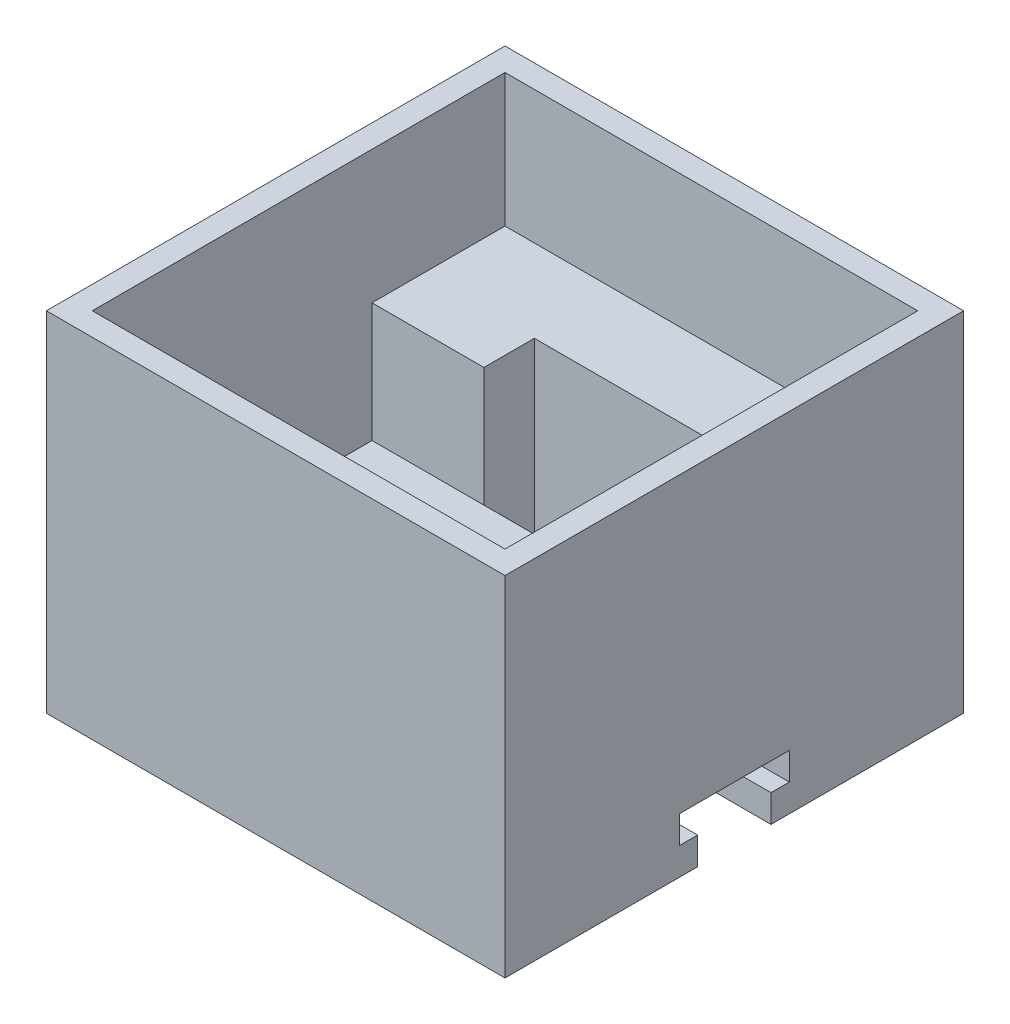
SolidWorks part; units mm, degrees
ref_plane "Front Plane" through (0, 0, 0) normal (0, 0, 1) x (1, 0, 0)
ref_plane "Top Plane" through (0, 0, 0) normal (0, 1, 0) x (1, 0, 0)
ref_plane "Right Plane" through (0, 0, 0) normal (1, 0, 0) x (0, 0, -1)
sketch "Sketch1" plane through (0, 0, 0) normal (0, 1, 0) x (1, 0, 0)
  line L1 (25, 25) -> (-25, 25)
  line L2 (25, 25) -> (25, -25)
  line L3 (25, -25) -> (-25, -25)
  line L4 (-25, 25) -> (-25, -25)
  line L5 (25, 25) -> (-25, -25) construction
  line L6 (25, -25) -> (-25, 25) construction
  point P0 (0, 0)
  dimension "D1" = 50
  dimension "D2" = 50
extrude "Boss-Extrude1" add sketch "Sketch1" along normal blind 38
shell "Shell1" thickness 2.5
sketch "Sketch2" plane through (0, 2.5, 0) normal (0, 1, 0) x (1, 0, 0)
  line L1 (9.676, 17.0496) -> (-10.324, 17.0496) construction
  line L2 (9.676, 17.0496) -> (9.676, -16.9504) construction
  line L3 (-10.3, -16.9504) -> (-10.324, -16.9504) construction
  line L4 (-10.324, 17.0496) -> (-10.324, -16.9504) construction
  line L5 (-10.3, 8) -> (-22.5, 8)
  line L6 (-22.5, 22.5) -> (-22.5, -22.5) construction
  line L7 (-22.5, 8) -> (-22.5, 22.5)
  line L8 (-22.5, 22.5) -> (0, 22.5)
  line L9 (22.5, 22.5) -> (-22.5, 22.5) construction
  line L11 (-10.3, 8) -> (-10.3, 13.5)
  line L12 (-10.3, 13.5) -> (0, 13.5)
  line L13 (22.5, -22.5) -> (22.5, 22.5) construction
  line L14 (22.5, 8) -> (22.5, 22.5)
  line L15 (10.3, 8) -> (22.5, 8)
  line L16 (10.3, 8) -> (10.3, 13.5)
  line L17 (10.3, 13.5) -> (0, 13.5)
  line L19 (22.5, 22.5) -> (0, 22.5)
  line L20 (10.3, -13.6) -> (22.5, -13.6)
  line L22 (10.0266, -9.8035) -> (10.0241, -17.0234) construction
  line L27 (-22.5, -13.6) -> (-22.5, -22.5)
  line L28 (-10.3, -13.6) -> (-22.5, -13.6)
  line L29 (-10.3, -13.6) -> (-10.3, -20.79)
  line L30 (-10.3, -20.79) -> (0.1901, -20.79)
  line L32 (-22.5, -22.5) -> (0.1901, -22.5)
  line L33 (-10.324, 17.0496) -> (-10.324, 9.8396) construction
  line L34 (10.3, -13.6) -> (10.3, -20.79)
  line L35 (9.676, -16.9504) -> (-10.3, -16.9504) construction
  line L36 (10.3, -20.79) -> (0.1901, -20.79)
  line L38 (22.5, -22.5) -> (0.1901, -22.5)
  line L39 (22.5, -13.6) -> (22.5, -22.5)
  line L40 (22.5, -22.5) -> (22.5, 22.5) construction
  point P0 (0, 0)
  line M19 (-22.5, 22.5) -> (-22.5, -22.5)
  line M20 (-22.5, -22.5) -> (22.5, -22.5)
  line M21 (22.5, -22.5) -> (22.5, 22.5)
  line M22 (22.5, 22.5) -> (-22.5, 22.5)
  dimension "D1" = 34
  dimension "D3" = 12.2
  dimension "D4" = 12.2
  dimension "D5" = 14.5
  dimension "D6" = 8.9
  dimension "D7" = 9
  dimension "D9" = 1.71
sketch "Sketch3" plane through (0, 2.5, 0) normal (0, 1, 0) x (1, 0, 0)
  line L0 (22.5, -8) -> (22.5, 8)
  line L1 (22.5, -22.5) -> (22.5, 22.5) construction
  line L2 (22.5, 8) -> (22.5, -8)
  line L3 (22.5, 8) -> (-22.5, 8)
  line L4 (22.5, -8) -> (-22.5, -8)
  line L5 (-22.5, 8) -> (-22.5, -8)
  line L6 (-22.5, 22.5) -> (-22.5, -22.5) construction
  point P4 (22.5, 0)
  point P6 (22.5, 0)
  line M6 (-22.5, 22.5) -> (-22.5, -22.5)
  line M8 (22.5, -22.5) -> (22.5, 22.5)
  dimension "D1" = 16
extrude "Boss-Extrude2" add sketch "Sketch2" along normal blind 21 contours L34 L36 L30 L29 L28 L20 M19 M20 M21 | L17 L16 L15 L5 L11 L12 M21 M22 M19
extrude "Boss-Extrude3" add sketch "Sketch3" along normal blind 8 contours L4 L3 M8 M6
sketch "Sketch4" plane through (0, 0, 0) normal (0, -1, 0) x (1, 0, 0)
  line L4 (25, -4) -> (-7.5, -4)
  line L5 (22.5, -8) -> (25, -8) construction
  line L6 (22.5, 8) -> (25, 8) construction
  line L7 (22.5, 0) -> (25, 0)
  line L8 (25, 25) -> (25, -25) construction
  line L9 (-7.5, -4) -> (-7.5, 4)
  line L10 (-7.5, 4) -> (25, 4)
  line L11 (25, 4) -> (25, -4)
  point P10 (25, 0)
  dimension "D1" = 8
  dimension "D2" = 32.5
extrude "Cut-Extrude1" cut sketch "Sketch4" against normal blind 3
ref_plane "Plane1" through (0, 3, 0) normal (0, -1, 0) x (-1, 0, 0)
sketch "Sketch7" plane through (0, 3, 0) normal (0, -1, 0) x (-1, 0, 0)
  line L5 (-25, 4) -> (-25, -4) construction
  line L6 (-25, -6) -> (-25, 6)
  line L7 (-25, -6) -> (7.5, -6)
  line L8 (-25, 6) -> (7.5, 6)
  line L9 (7.5, -6) -> (7.5, 6)
  line L10 (-25, -25) -> (-25, -4) construction
  line L11 (-25, 4) -> (-25, 25) construction
  point P4 (-25, 0)
  point P11 (-25, 0)
  dimension "D1" = 12
  dimension "D2" = 32.5
extrude "Cut-Extrude2" cut sketch "Sketch7" against normal blind 3
